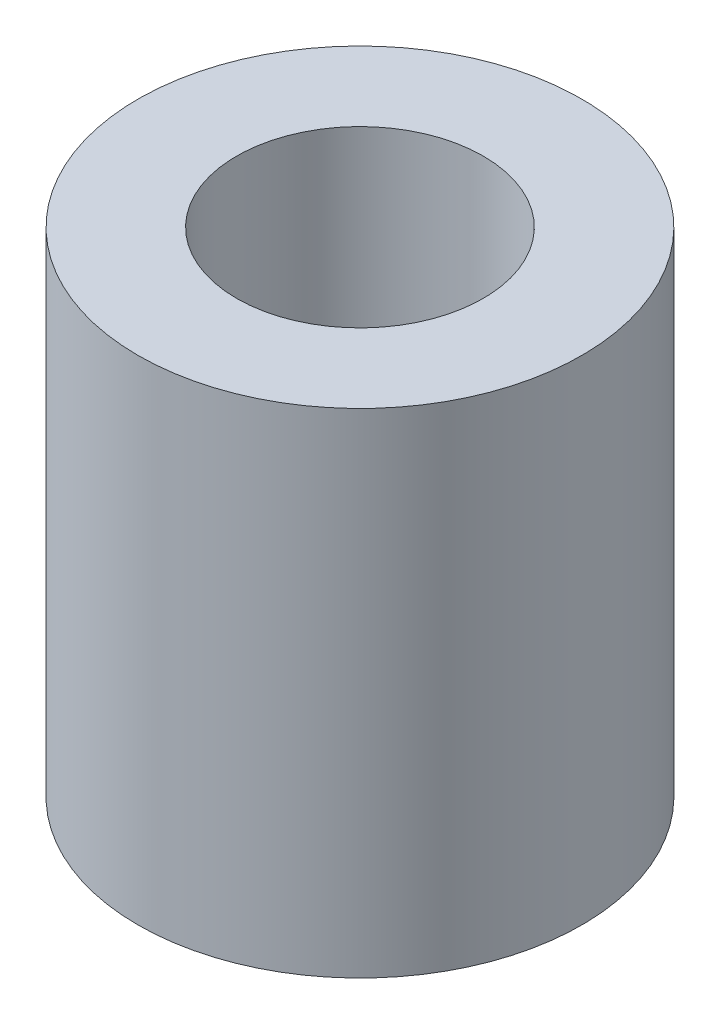
SolidWorks part; units mm, degrees
material "AISI 304"
ref_plane "Front" through (0, 0, 0) normal (0, 0, 1) x (1, 0, 0)
ref_plane "Top" through (0, 0, 0) normal (0, 1, 0) x (1, 0, 0)
ref_plane "Right" through (0, 0, 0) normal (1, 0, 0) x (0, 0, -1)
sketch "Sketch1" plane through (0, 0, 0) normal (0, 1, 0) x (1, 0, 0)
  circle A0 centre (0, 0) radius 4.5
extrude "Boss-Extrude1" add sketch "Sketch1" along normal blind 10
sketch "Sketch2" plane through (0, 10, 0) normal (0, 1, 0) x (1, 0, 0)
  circle A0 centre (0, 0) radius 2.5
extrude "Cut-Extrude1" cut sketch "Sketch2" against normal through all
